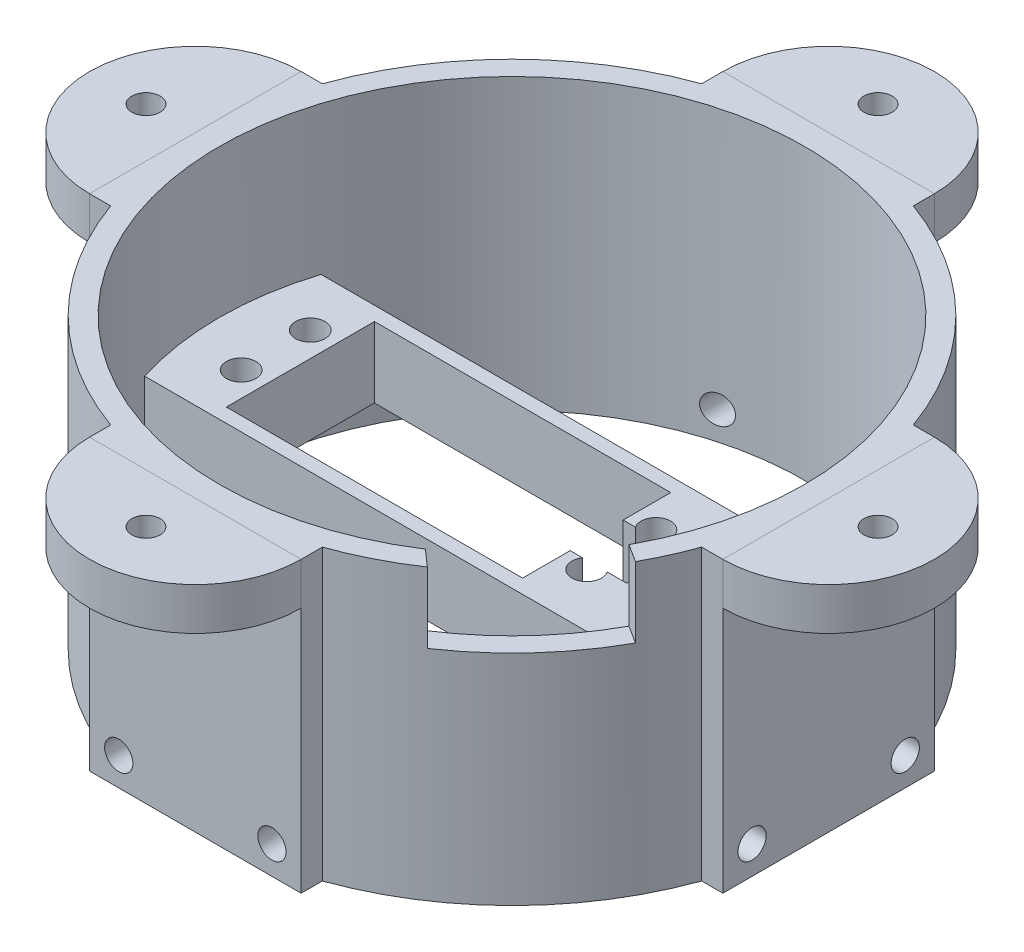
SolidWorks part; units mm, degrees
ref_plane "Front Plane" through (0, 0, 0) normal (0, 0, 1) x (1, 0, 0)
ref_plane "Top Plane" through (0, 0, 0) normal (0, 1, 0) x (1, 0, 0)
ref_plane "Right Plane" through (0, 0, 0) normal (1, 0, 0) x (0, 0, -1)
sketch "Sketch1" plane through (0, 0, 0) normal (0, 1, 0) x (1, 0, 0)
  circle A0 centre (0, 0) radius 44.5
  circle A1 centre (0, 0) radius 41.5
  dimension "D1" = 3
  dimension "D2" = 83
extrude "Boss-Extrude1" add sketch "Sketch1" along normal blind 41
sketch "Sketch2" plane through (0, 0, 0) normal (0, 1, 0) x (1, 0, 0)
  line L0 (-39.5727, 12.5) -> (39.5727, 12.5)
  line L1 (-39.5727, -12.5) -> (39.5727, -12.5)
  line L2 (-9, 10.5) -> (-9, -15.318) construction
  line L3 (-30, 10.5) -> (12, 10.5)
  line L4 (-30, 10.5) -> (-30, -10.5)
  line L5 (-30, -10.5) -> (12, -10.5)
  line L6 (12, 10.5) -> (12, -10.5)
  circle A0 centre (0, 0) radius 41.5 construction
  arc A1 (-39.5727, 12.5) -> (-39.5727, -12.5) centre (-3.1584, 0) ccw
  arc A2 (39.5727, 12.5) -> (39.5727, -12.5) centre (3.1584, 0) cw
  circle A3 centre (15.5, 4.9) radius 2.1
  circle A4 centre (15.5, -4.9) radius 2.1
  circle A7 centre (-33.5, 4.9) radius 2.1
  circle A8 centre (-33.5, -4.9) radius 2.1
  point P6 (0, 0)
  dimension "D5" = 4.2
  dimension "D6" = 4.9
  dimension "D7" = 4.9
  dimension "D11" = 0
  dimension "D1" = 12.5
  dimension "D2" = 12.5
  dimension "D3" = 21
  dimension "D4" = 42
  dimension "D8" = 10.5
  dimension "D9" = 12
  dimension "D10" = 3.5
extrude "Boss-Extrude2" add sketch "Sketch2" along normal blind 20
sketch "Sketch3" plane through (0, 0, 0) normal (0, 1, 0) x (1, 0, 0)
  line L0 (0, 0) -> (0, 56.6556) construction
  line L1 (0, 44.8957) -> (-15, 44.8957)
  line L2 (-15, 44.8957) -> (-15, 41.8957)
  line L3 (0, 44.8957) -> (15, 44.8957)
  line L4 (15, 44.8957) -> (15, 41.8957)
  circle A0 centre (0, 0) radius 44.5 construction
  arc A1 (-15, 41.8957) -> (15, 41.8957) centre (0, 0) cw
  dimension "D1" = 15
  dimension "D2" = 15
  dimension "D3" = 3
extrude "Boss-Extrude3" add sketch "Sketch3" along normal blind 41
pattern_circular "CirPattern1" count 4 over 360 about axis through (0, 0, 0) along (0, 1, 0) of "Boss-Extrude3"
sketch "Sketch4" plane through (-44.8957, 0, 0) normal (-1, 0, 0) x (0, 0, 1)
  line L1 (0, 37.0728) -> (0, -4.8522) construction
  line L2 (-15, 0) -> (15, 0) construction
  line L3 (15, 41) -> (15, 0) construction
  circle A0 centre (10.8598, 4) radius 2
  circle A2 centre (-10.8598, 4) radius 2
  dimension "D1" = 4
  dimension "D2" = 4
  dimension "D3" = 4.1402
extrude "Cut-Extrude1" cut sketch "Sketch4" against normal blind 7
sketch "Sketch5" plane through (0, 0, 0) normal (0, 1, 0) x (1, 0, 0)
  line L0 (-39.5727, 12.5) -> (39.5727, 12.5)
  line L1 (-39.5727, -12.5) -> (39.5727, -12.5)
  arc A0 (-39.5727, 12.5) -> (-39.5727, -12.5) centre (0, 0) ccw
  arc A1 (39.5727, -12.5) -> (39.5727, 12.5) centre (0, 0) ccw
extrude "Cut-Extrude2" cut sketch "Sketch5" along normal blind 10
pattern_circular "CirPattern2" count 4 over 360 about axis through (0, 41, 0) along (0, -1, 0) of "Cut-Extrude1"
sketch "Sketch6" plane through (0, 41, 0) normal (0, 1, 0) x (1, 0, 0)
  line L0 (-44.8957, 15) -> (-44.8957, -15)
  line L1 (44.8957, -15) -> (44.8957, 15) construction
  line L2 (-15, 44.8957) -> (15, 44.8957)
  line L3 (44.8957, 15) -> (44.8957, -15)
  line L4 (15, -44.8957) -> (-15, -44.8957)
  arc A0 (-44.8957, 15) -> (-44.8957, -15) centre (-44.8957, 0) ccw
  circle A1 centre (-51.8957, 0) radius 2
  arc A2 (44.8957, 15) -> (44.8957, -15) centre (44.8957, 0) cw
  arc A3 (15, -44.8957) -> (-15, -44.8957) centre (0, -44.8957) cw
  arc A4 (-15, 44.8957) -> (15, 44.8957) centre (0, 44.8957) cw
  circle A5 centre (51.8957, 0) radius 2
  circle A6 centre (0, 51.8957) radius 2
  circle A7 centre (0, -51.8957) radius 2
  dimension "D1" = 4
  dimension "D2" = 7
  dimension "D3" = 7
  dimension "D4" = 7
  dimension "D5" = 7
extrude "Boss-Extrude4" add sketch "Sketch6" against normal blind 6 separate body
sketch "Sketch8" plane through (0, 0, 0) normal (0, 1, 0) x (1, 0, 0)
  line L0 (12, 3.75) -> (20, 3.75)
  line L1 (12, -10.5) -> (12, 10.5) construction
  line L2 (20, 3.75) -> (20, -3.75)
  line L3 (20, -3.75) -> (12, -3.75)
  line L4 (12, 3.75) -> (12, -3.75)
  dimension "D1" = 8
  dimension "D2" = 3.75
  dimension "D3" = 3.75
extrude "Cut-Extrude3" cut sketch "Sketch8" along normal blind 60
sketch "Sketch9" plane through (0, 41, 0) normal (0, 1, 0) x (1, 0, 0)
  line L0 (36.4415, -19.8562) -> (38.9762, -21.4734)
  line L1 (24.8878, -36.8897) -> (22.5565, -34.8347)
  arc A0 (36.4415, -19.8562) -> (22.5565, -34.8347) centre (0, 0) cw
  circle A1 centre (0, 0) radius 41.5 construction
  arc A2 (38.9762, -21.4734) -> (24.8878, -36.8897) centre (0, 0) cw
  arc A3 (15, -41.8957) -> (41.8957, -15) centre (0, 0) ccw construction
extrude "Cut-Extrude4" cut sketch "Sketch9" against normal blind 10
